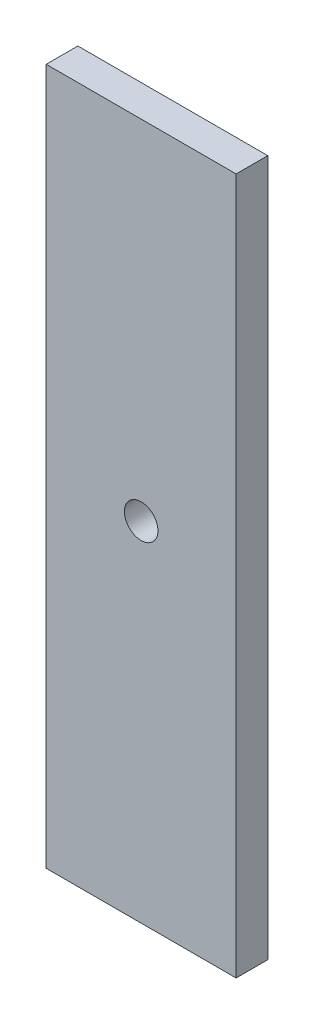
SolidWorks part; units mm, degrees
ref_plane "Front Plane" through (0, 0, 0) normal (0, 0, 1) x (1, 0, 0)
ref_plane "Top Plane" through (0, 0, 0) normal (0, 1, 0) x (1, 0, 0)
ref_plane "Right Plane" through (0, 0, 0) normal (1, 0, 0) x (0, 0, -1)
sketch "Sketch1" plane through (0, 0, 0) normal (0, 0, 1) x (1, 0, 0)
  line L1 (-19.05, -69.85) -> (19.05, -69.85)
  line L2 (-19.05, -69.85) -> (-19.05, 69.85)
  line L3 (-19.05, 69.85) -> (19.05, 69.85)
  line L4 (19.05, -69.85) -> (19.05, 69.85)
  line L5 (-19.05, -69.85) -> (19.05, 69.85) construction
  line L6 (-19.05, 69.85) -> (19.05, -69.85) construction
  circle A0 centre (0, 0) radius 3.3655
  point P0 (0, 0)
  dimension "D3" = 6.731
  dimension "D1" = 139.7
  dimension "D2" = 38.1
extrude "Boss-Extrude1" add sketch "Sketch1" along normal blind 6.35
